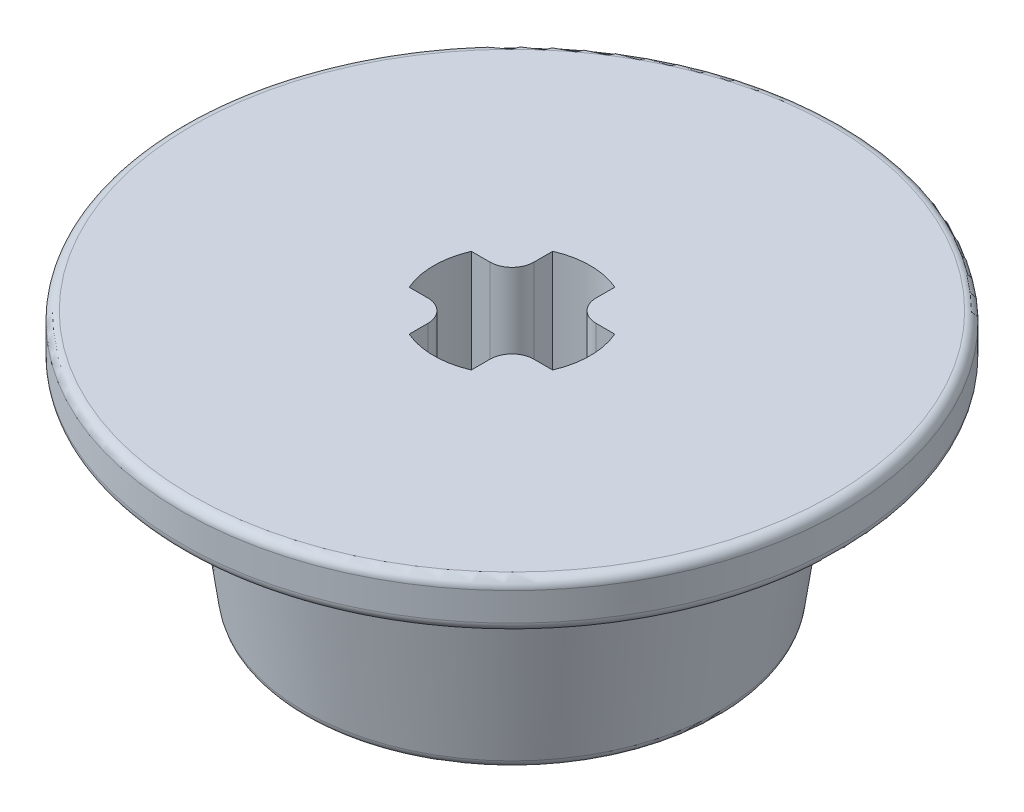
SolidWorks part; units mm, degrees
ref_plane "Front Plane" through (0, 0, 0) normal (0, 0, 1) x (1, 0, 0)
ref_plane "Top Plane" through (0, 0, 0) normal (0, 1, 0) x (1, 0, 0)
ref_plane "Right Plane" through (0, 0, 0) normal (1, 0, 0) x (0, 0, -1)
sketch "Sketch1" plane through (0, 0, 0) normal (0, 1, 0) x (1, 0, 0)
  line L2 (0, 0) -> (0, 47.5777) construction
  line L3 (0, 0) -> (50000, 0) construction
  line L6 (-0.89, 0.89) -> (0, 0) construction
  line L7 (0, 0) -> (0.89, 0.89) construction
  line L12 (2.39, 0) -> (2.39, 3.5727) construction
  line L13 (0, 2.39) -> (50000, 2.39) construction
  line L14 (-2.39, 0.4111) -> (-2.39, -49999.5889) construction
  line L15 (0.2318, -2.39) -> (-49999.7682, -2.39) construction
  line L16 (0, 0) -> (-0.89, -0.89) construction
  line L17 (0, 0) -> (0.89, -0.89) construction
  line L18 (-0.99, 0.99) -> (-2.2847, 0.99)
  line L19 (-2.2847, -0.99) -> (-0.99, -0.99)
  line L20 (-0.99, -0.99) -> (-0.99, -2.2847)
  line L21 (0.99, -2.2847) -> (0.99, -0.99)
  line L22 (0.99, -0.99) -> (2.2842, -0.99)
  line L23 (0.99, 0.99) -> (2.2842, 0.99)
  line L24 (0.99, 2.2875) -> (0.99, 0.99)
  line L25 (-0.99, 2.2875) -> (-0.99, 0.99)
  arc A4 (-2.2847, 0.99) -> (-2.2847, -0.99) centre (0, 0) ccw
  arc A5 (-0.99, -2.2847) -> (0.99, -2.2847) centre (0, 0) ccw
  arc A6 (2.2842, 0.99) -> (2.2842, -0.99) centre (0, 0) cw
  arc A7 (-0.99, 2.2875) -> (0.99, 2.2875) centre (0, 0) cw
  point P0 (0, 0)
  point P15 (0, 2.39)
  point P24 (2.39, 0)
  point P29 (-2.39, 0)
  point P30 (0, -2.39)
  line B0 (-0.89, 2.2181) -> (-0.89, 0.89) construction
  line B1 (-0.89, 0.89) -> (-2.2181, 0.89) construction
  line B2 (0.89, 2.2181) -> (0.89, 0.89) construction
  line B3 (0.89, 0.89) -> (2.2181, 0.89) construction
  line B4 (-2.2181, -0.89) -> (-0.89, -0.89) construction
  line B5 (-0.89, -0.89) -> (-0.89, -2.2181) construction
  line B6 (0.89, -2.2181) -> (0.89, -0.89) construction
  line B7 (0.89, -0.89) -> (2.2181, -0.89) construction
  arc B8 (-0.89, 2.2181) -> (0.89, 2.2181) centre (0, 0) cw construction
  arc B9 (-2.2181, 0.89) -> (-2.2181, -0.89) centre (0, 0) ccw construction
  arc B10 (2.2181, 0.89) -> (2.2181, -0.89) centre (0, 0) cw construction
  arc B11 (-0.89, -2.2181) -> (0.89, -2.2181) centre (0, 0) ccw construction
sketch_block_instance "Lego Axle - Unfilleted-1"
sketch_block "Lego Axle - Unfilleted" parameters "D9"=2.44, "D14"=2.4794, "D15"=2.44, "D1"=10.5762, "D2"=12.3972, "D3"=62.5785, "D4"=1.2287, "D5"=12.9019, "D6"=1.0841, "D7"=1.3117, "D8"=1.78, "D10"=1.3117, "D11"=1.3831, "D12"=0.0285, "D13"=1.3442, "D16"=0.0996
sketch "Sketch2" plane through (0, 0, 0) normal (0, 0, 1) x (1, 0, 0)
  line L0 (0, 0) -> (10.5, 0)
  line L1 (200000.2318, 0) -> (-249999.7682, 0) construction
  line L2 (10.5, 0) -> (10.5, -1.5)
  line L3 (10.5, -1.5) -> (7.5, -1.5)
  line L4 (7.5, -1.5) -> (6.5865, -8)
  line L5 (6.5865, -8) -> (0, -8)
  line L6 (0, -8) -> (0, 0)
  line L7 (0, 0) -> (0, 50000) construction
  dimension "D1" = 15
  dimension "D2" = 8
  dimension "D3" = 8
  dimension "D4" = 1.5
  dimension "D5" = 3
revolve "Revolve1" add sketch "Sketch2" angle 360 about L7
extrude "Cut-Extrude1" cut sketch "Sketch1" against normal through all
fillet "Fillet1" radius 0.7 4 edges at (-0.99, -4, 0.99) (0.99, -4, 0.99) (0.99, -4, -0.99) (-0.99, -4, -0.99)
fillet "Fillet2" radius 0.3 4 edges at (0, -8, -6.5865) (0, 0, -10.5) (0, -1.5, -7.5) (0, -1.5, -10.5)
